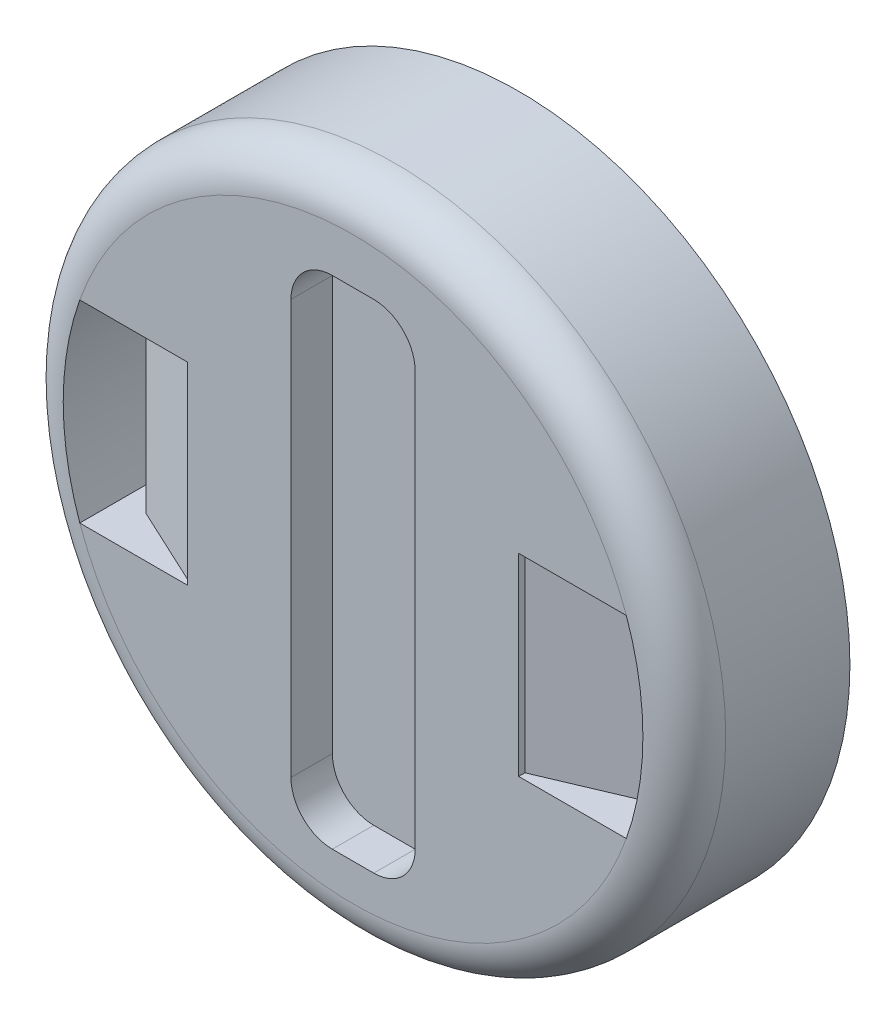
SolidWorks part; units mm, degrees
material "AISI 304"
ref_plane "Front Plane" through (0, 0, 0) normal (0, 0, 1) x (1, 0, 0)
ref_plane "Top Plane" through (0, 0, 0) normal (0, 1, 0) x (1, 0, 0)
ref_plane "Right Plane" through (0, 0, 0) normal (1, 0, 0) x (0, 0, -1)
sketch "草图1" plane through (0, 0, 12) normal (0, 0, -1) x (-1, 0, 0)
  circle A0 centre (0, 0) radius 8
extrude "凸台-拉伸1" add sketch "草图1" against normal blind 4
fillet "圆角1" radius 1 1 edges at (-8, 0, 16)
sketch "草图3" plane through (0, 0, 16) normal (0, 0, 1) x (1, 0, 0)
  line L0 (0, 8) -> (0, -8) construction
  line L1 (-1.5, 5.8946) -> (1.5, 5.8946)
  line L2 (-1.5, 5.8946) -> (-1.5, -6.1054)
  line L3 (-1.5, -6.1054) -> (1.5, -6.1054)
  line L4 (1.5, 5.8946) -> (1.5, -6.1054)
  point P5 (0, 5.8946)
extrude "切除-拉伸1" cut sketch "草图3" against normal blind 1
fillet "圆角2" radius 1 4 edges at (1.5, -6.1054, 15.5) (-1.5, -6.1054, 15.5) (1.5, 5.8946, 15.5) (-1.5, 5.8946, 15.5)
sketch "草图4" plane through (0, 0, 16) normal (0, 0, 1) x (1, 0, 0)
  line L1 (-6.5997, 2.3333) -> (-4, 2.3333)
  line L2 (-6.5997, -2.3333) -> (-4, -2.3333)
  line L3 (4, -2.3333) -> (6.5997, -2.3333)
  line L5 (4, 2.3333) -> (6.5997, 2.3333)
  line L6 (-4, 2.3333) -> (-4, -2.3333)
  line L8 (4, 2.3333) -> (4, -2.3333)
  arc A1 (-6.5997, 2.3333) -> (-6.5997, -2.3333) centre (0, 0) ccw
  arc A4 (6.5997, -2.3333) -> (6.5997, 2.3333) centre (0, 0) ccw
extrude "切除-拉伸2" cut sketch "草图4" against normal blind 1
chamfer "倒角2" distance 2 angle 25 1 edges at (-4, 0, 15)
chamfer "倒角5" distance 2 angle 23 1 edges at (4, 0, 15)
sketch "草图6" plane through (0, 0, 15) normal (0, 0, 1) x (1, 0, 0)
  line L0 (-6.5997, -2.3333) -> (-6, -2.3333) construction
  line L1 (-6, -2.3333) -> (-6, 2.3333) construction
  line L2 (-6, 2.3333) -> (-6.5997, 2.3333) construction
  line L3 (6.5997, 2.3333) -> (6, 2.3333) construction
  line L4 (6, 2.3333) -> (6, -2.3333) construction
  line L5 (6, -2.3333) -> (6.5997, -2.3333) construction
  line L6 (-6.5997, -2.3333) -> (-6, -2.3333)
  line L7 (-6, -2.3333) -> (-6, 2.3333)
  line L8 (-6, 2.3333) -> (-6.5997, 2.3333)
  line L9 (6.5997, 2.3333) -> (6, 2.3333)
  line L10 (6, 2.3333) -> (6, -2.3333)
  line L11 (6, -2.3333) -> (6.5997, -2.3333)
  arc A0 (-6.5997, 2.3333) -> (-6.5997, -2.3333) centre (0, 0) ccw construction
  arc A1 (6.5997, -2.3333) -> (6.5997, 2.3333) centre (0, 0) ccw construction
  arc A2 (-6.5997, 2.3333) -> (-6.5997, -2.3333) centre (0, 0) ccw
  arc A3 (6.5997, -2.3333) -> (6.5997, 2.3333) centre (0, 0) ccw
extrude "切除-拉伸3" cut sketch "草图6" against normal blind 8
sketch "草图7" plane through (0, 0, 12) normal (0, 0, -1) x (-1, 0, 0)
  circle A0 centre (0, 0) radius 7
extrude "切除-拉伸4" cut sketch "草图7" against normal blind 2
